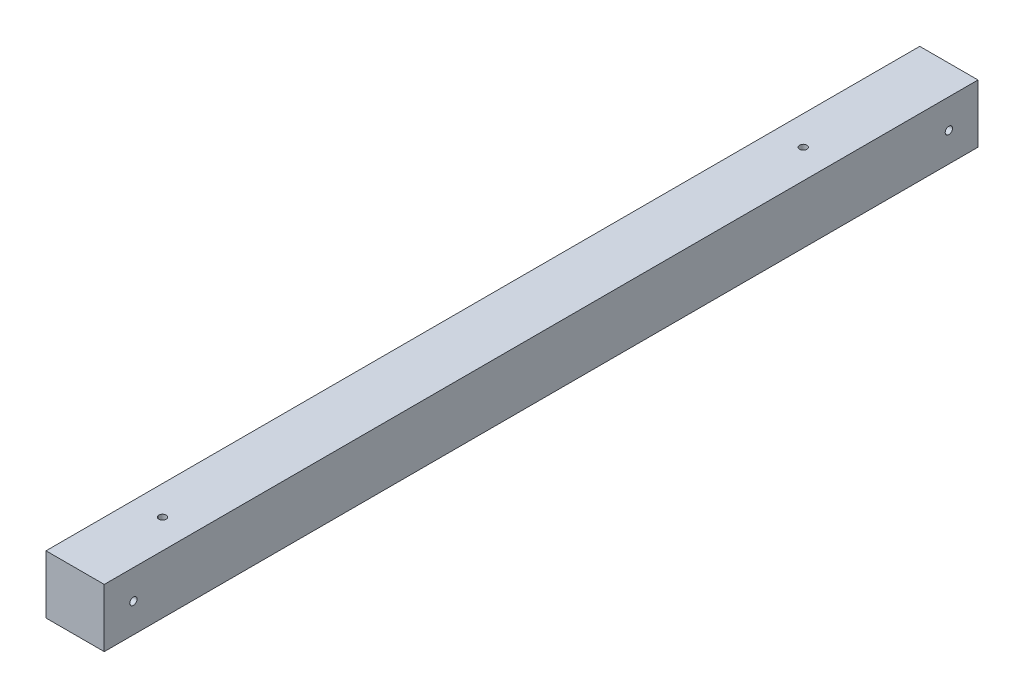
SolidWorks part; units mm, degrees
ref_plane "Front Plane" through (0, 0, 0) normal (0, 0, 1) x (1, 0, 0)
ref_plane "Top Plane" through (0, 0, 0) normal (0, 1, 0) x (1, 0, 0)
ref_plane "Right Plane" through (0, 0, 0) normal (1, 0, 0) x (0, 0, -1)
sketch "Sketch6" plane through (0, 0, 0) normal (0, 0, 1) x (1, 0, 0)
  line L1 (12.7, -12.7) -> (-12.7, -12.7)
  line L2 (12.7, -12.7) -> (12.7, 12.7)
  line L3 (12.7, 12.7) -> (-12.7, 12.7)
  line L4 (-12.7, -12.7) -> (-12.7, 12.7)
  line L5 (12.7, -12.7) -> (-12.7, 12.7) construction
  line L6 (12.7, 12.7) -> (-12.7, -12.7) construction
  point P0 (0, 0)
  dimension "D1" = 25.4
extrude "Boss-Extrude1" add sketch "Sketch6" along normal blind 381
hole_wizard "1/8 (0.125) Diameter Hole2" positions "Sketch7" profile "Sketch8" hole size "1/8" standard "ANSI Inch" end condition through all
sketch "Sketch7" plane through (12.7, 0, 0) normal (1, 0, 0) x (0, 0, -1)
  line L0 (0, 0) -> (-381, 0) construction
  line L1 (-381, -12.7) -> (-381, 12.7) construction
  point P7 (-368.3, 0)
  point P9 (-12.7, 0)
  dimension "D1" = 12.7
  dimension "D2" = 12.7
sketch "Sketch8" plane through (12.7, 0, 12.7) normal (0, 1, 0) x (0, 0, -1)
  line L0 (0, 0) -> (0, 25.4)
  line L1 (0, 25.4) -> (1.5875, 25.4)
  line L2 (1.5875, 25.4) -> (1.5875, 0)
  line L5 (1.5875, 0) -> (0, 0)
  line L11 (0, -6.35) -> (0, 107.95) construction
  dimension "Thru Hole Dia." = 3.175
  dimension "Thru Hole Depth" = 25.4
hole_wizard "1/8 (0.125) Diameter Hole3" positions "Sketch9" profile "Sketch10" hole size "1/8" standard "ANSI Inch" end condition through all
sketch "Sketch9" plane through (0, 12.7, 0) normal (0, 1, 0) x (1, 0, 0)
  line L0 (0, 0) -> (0, -381) construction
  line L1 (12.7, -381) -> (-12.7, -381) construction
  point P7 (0, -342.9)
  point P9 (0, -63.5)
  dimension "D1" = 63.5
  dimension "D2" = 38.1
sketch "Sketch10" plane through (0, 12.7, 63.5) normal (1, 0, 0) x (0, 0, 1)
  line L0 (0, 0) -> (0, 25.4)
  line L1 (0, 25.4) -> (1.5875, 25.4)
  line L2 (1.5875, 25.4) -> (1.5875, 0)
  line L5 (1.5875, 0) -> (0, 0)
  line L11 (0, -6.35) -> (0, 107.95) construction
  dimension "Thru Hole Dia." = 3.175
  dimension "Thru Hole Depth" = 25.4
